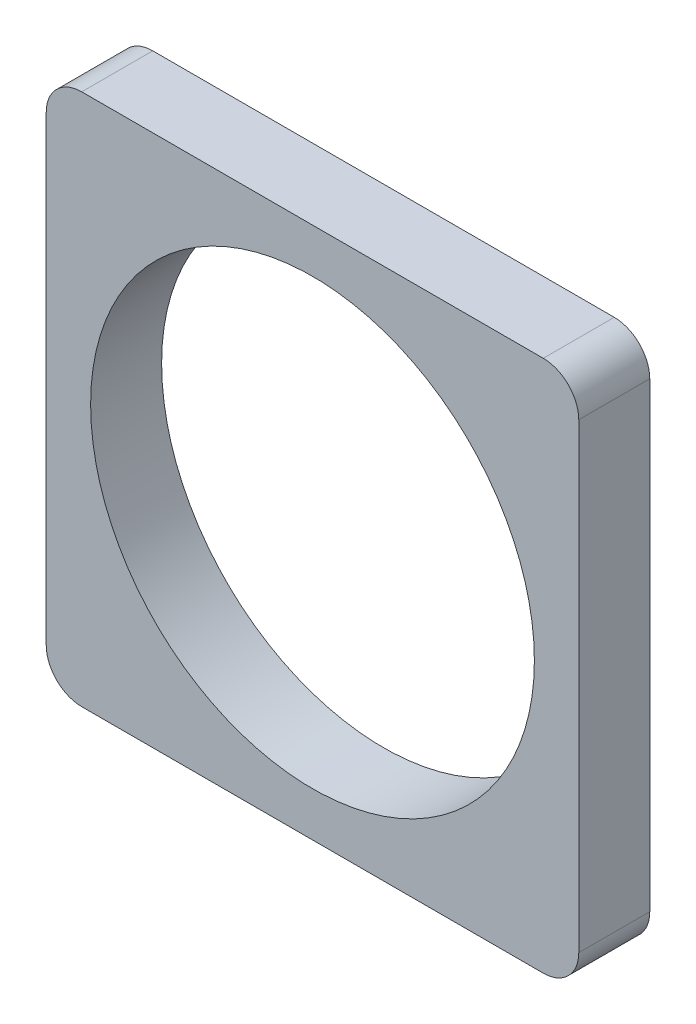
SolidWorks part; units mm, degrees
ref_plane "Front Plane" through (0, 0, 0) normal (0, 0, 1) x (1, 0, 0)
ref_plane "Top Plane" through (0, 0, 0) normal (0, 1, 0) x (1, 0, 0)
ref_plane "Right Plane" through (0, 0, 0) normal (1, 0, 0) x (0, 0, -1)
sketch "Sketch1" plane through (0, 0, 0) normal (0, 0, 1) x (1, 0, 0)
  line L1 (0, 0) -> (30, 0)
  line L2 (0, 0) -> (0, 30)
  line L3 (0, 30) -> (30, 30)
  line L4 (30, 0) -> (30, 30)
  circle A0 centre (15, 15) radius 12.5
  dimension "D3" = 25
  dimension "D4" = 15
  dimension "D5" = 15
  dimension "D1" = 30
  dimension "D2" = 30
extrude "Boss-Extrude1" add sketch "Sketch1" along normal blind 4
fillet "Fillet1" radius 2 4 edges at (30, 0, 2) (0, 0, 2) (0, 30, 2) (30, 30, 2)
